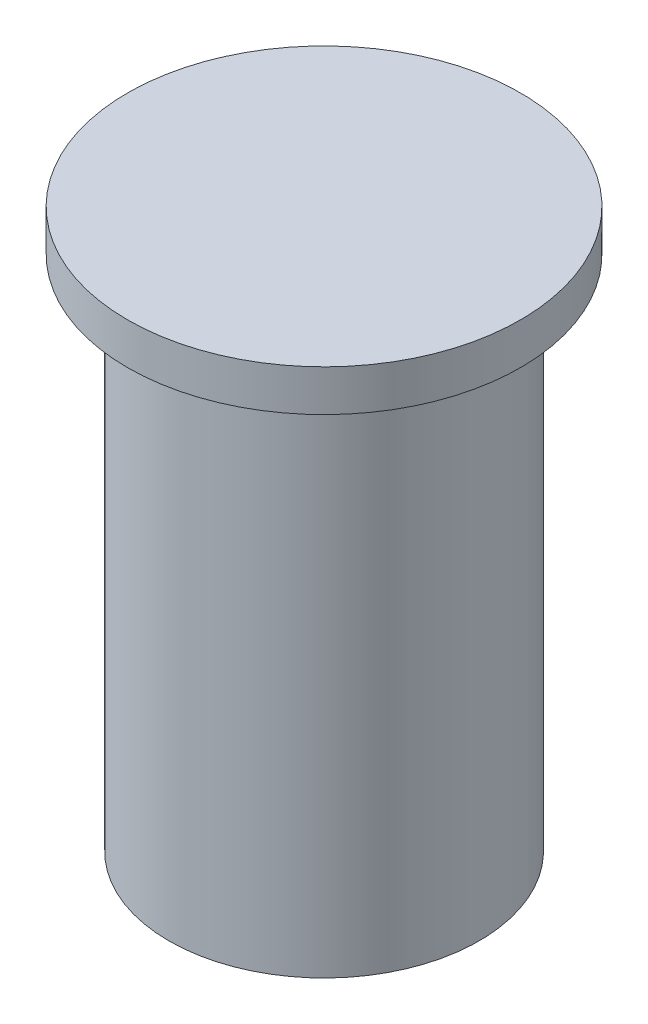
SolidWorks part; units mm, degrees
ref_plane "Front Plane" through (0, 0, 0) normal (0, 0, 1) x (1, 0, 0)
ref_plane "Top Plane" through (0, 0, 0) normal (0, 1, 0) x (1, 0, 0)
ref_plane "Right Plane" through (0, 0, 0) normal (1, 0, 0) x (0, 0, -1)
sketch "Sketch1" plane through (0, 0, 0) normal (1, 0, 0) x (0, 0, -1)
  line L0 (0, 0.4) -> (-1.9, 0.4)
  line L1 (0, 55) -> (0, -55) construction
  line L2 (-1.9, 0.4) -> (-1.9, 0)
  line L3 (-1.9, 0) -> (-1.5, 0)
  line L4 (-1.5, 0) -> (-1.5, -5)
  line L5 (-1.5, -5) -> (0, -5)
  line L6 (0, 0.4) -> (0, -5)
  line L7 (55, 0) -> (-55, 0) construction
  dimension "D1" = 1.5
  dimension "D2" = 1.9
  dimension "D3" = 0.4
  dimension "D4" = 5
revolve "Revolve1" add sketch "Sketch1" angle 360 about L6
